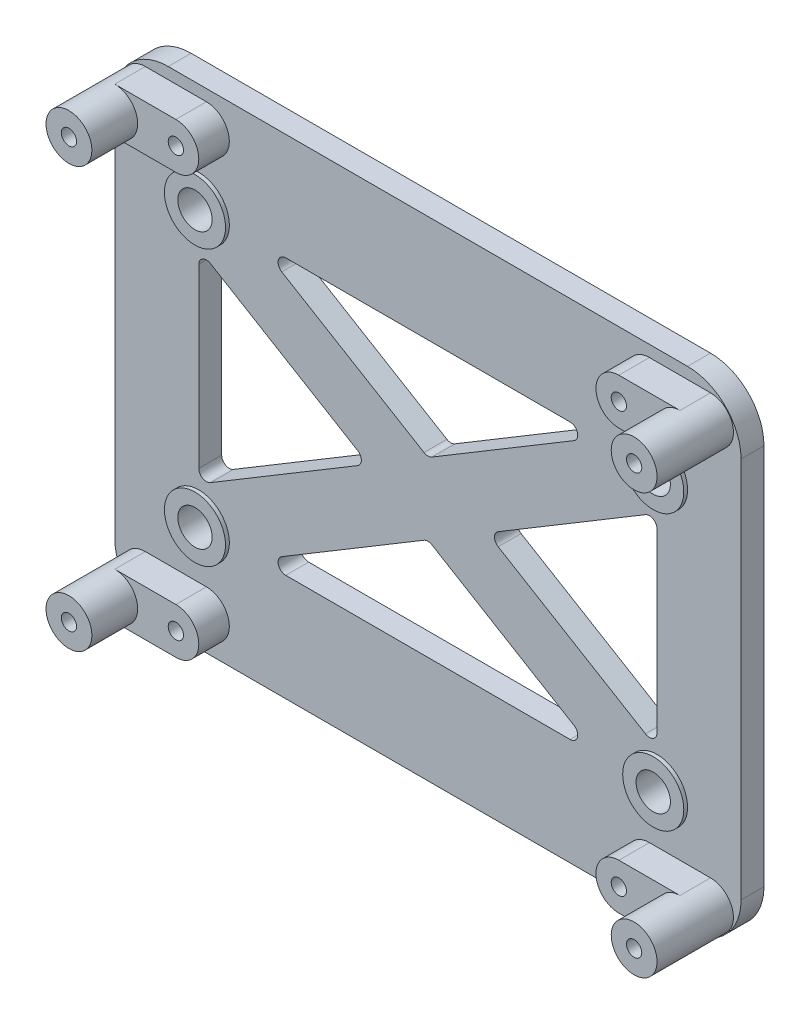
SolidWorks part; units mm, degrees
material "ABS"
ref_plane "Plano frontal" through (0, 0, 0) normal (0, 0, 1) x (1, 0, 0)
ref_plane "Plano superior" through (0, 0, 0) normal (0, 1, 0) x (1, 0, 0)
ref_plane "Plano direito" through (0, 0, 0) normal (1, 0, 0) x (0, 0, -1)
sketch "Esboço1" plane through (0, 0, 0) normal (0, 0, 1) x (1, 0, 0)
  line L1 (-41, -32) -> (41, -32)
  line L2 (-41, -32) -> (-41, 32)
  line L3 (-41, 32) -> (41, 32)
  line L4 (41, -32) -> (41, 32)
  line L5 (-41, -32) -> (41, 32) construction
  line L6 (-41, 32) -> (41, -32) construction
  point P0 (0, 0)
  dimension "D1" = 82
  dimension "D2" = 64
extrude "Ressalto-extrusão1" add sketch "Esboço1" along normal blind 3
sketch "Esboço2" plane through (0, 0, 3) normal (0, 0, 1) x (1, 0, 0)
  line L0 (0, 32) -> (0, -32) construction
  line L1 (41, 32) -> (-41, 32) construction
  line L2 (-41, -32) -> (41, -32) construction
  line L3 (-41, 0) -> (41, 0) construction
  line L4 (-41, 32) -> (-41, -32) construction
  line L5 (41, -32) -> (41, 32) construction
  circle A0 centre (-29, 27.5) radius 3
  circle A1 centre (-29, -27.5) radius 3
  circle A2 centre (29, -27.5) radius 3
  circle A3 centre (29, 27.5) radius 3
  circle A4 centre (-29, 27.5) radius 1
  circle A5 centre (29, 27.5) radius 1
  circle A6 centre (29, -27.5) radius 1
  circle A7 centre (-29, -27.5) radius 1
  dimension "D1" = 29
  dimension "D2" = 27.5
  dimension "D3" = 6
  dimension "D4" = 2
extrude "Ressalto-extrusão2" add sketch "Esboço2" along normal blind 4
sketch "Esboço3" plane through (0, 0, 3) normal (0, 0, 1) x (1, 0, 0)
  line L0 (0, 32) -> (0, -32) construction
  line L1 (41, 32) -> (-41, 32) construction
  line L2 (-41, -32) -> (41, -32) construction
  line L3 (-41, 0) -> (41, 0) construction
  line L4 (-41, 32) -> (-41, -32) construction
  line L5 (41, -32) -> (41, 32) construction
  circle A0 centre (-37, 27.5) radius 3
  circle A2 centre (-37, 27.5) radius 1
  circle A3 centre (37, 27.5) radius 1
  circle A4 centre (37, 27.5) radius 3
  circle A5 centre (37, -27.5) radius 3
  circle A6 centre (37, -27.5) radius 1
  circle A7 centre (-37, -27.5) radius 1
  circle A8 centre (-37, -27.5) radius 3
  dimension "D1" = 6
  dimension "D2" = 27.5
  dimension "D3" = 37
  dimension "D4" = 2
extrude "Ressalto-extrusão3" add sketch "Esboço3" along normal blind 10
sketch "Esboço4" plane through (0, 0, 3) normal (0, 0, 1) x (1, 0, 0)
  line L0 (0, 32) -> (0, -32) construction
  line L1 (41, 32) -> (-41, 32) construction
  line L2 (-41, -32) -> (41, -32) construction
  line L3 (-41, 0) -> (41, 0) construction
  line L4 (-41, 32) -> (-41, -32) construction
  line L5 (41, -32) -> (41, 32) construction
  circle A1 centre (-30, 18) radius 2.25
  circle A2 centre (30, 18) radius 2.25
  circle A5 centre (30, -18) radius 2.25
  circle A6 centre (-30, -18) radius 2.25
  dimension "D1" = 18
  dimension "D2" = 4.5
  dimension "D3" = 30
extrude "Corte-extrusão1" cut sketch "Esboço4" against normal through all
sketch "Esboço5" plane through (0, 0, 3) normal (0, 0, 1) x (1, 0, 0)
  line L0 (0, 32) -> (0, -32) construction
  line L1 (41, 32) -> (-41, 32) construction
  line L2 (-41, -32) -> (41, -32) construction
  line L3 (-41, 0) -> (41, 0) construction
  line L4 (-41, 32) -> (-41, -32) construction
  line L5 (41, -32) -> (41, 32) construction
  circle A0 centre (-30, 18) radius 2.25
  circle A1 centre (-30, 18) radius 4
  circle A2 centre (30, 18) radius 4
  circle A3 centre (30, 18) radius 2.25
  circle A4 centre (-30, -18) radius 4
  circle A5 centre (-30, -18) radius 2.25
  circle A6 centre (30, -18) radius 2.25
  circle A7 centre (30, -18) radius 4
  dimension "D1" = 8
  dimension "D2" = 4.5
extrude "Ressalto-extrusão4" add sketch "Esboço5" along normal blind 0.5
fillet "Filete1" radius 7 4 edges at (-41, -32, 1.5) (41, -32, 1.5) (41, 32, 1.5) (-41, 32, 1.5)
sketch "Esboço6" plane through (0, 0, 3) normal (0, 0, 1) x (1, 0, 0)
  line L0 (-30, 18) -> (30, -18) construction
  line L1 (-30, -18) -> (30, 18) construction
  line L2 (-30, 13.3352) -> (-7.7746, 0)
  line L3 (-22.2254, -18) -> (0, -4.6648)
  line L4 (-22.2254, 18) -> (0, 4.6648)
  line L5 (-30, -13.3352) -> (-7.7746, 0)
  line L6 (-22.2254, 18) -> (22.2254, 18)
  line L7 (-30, 13.3352) -> (-30, -13.3352)
  line L8 (-22.2254, -18) -> (22.2254, -18)
  line L9 (30, -13.3352) -> (30, 13.3352)
  line L10 (-27.942, 21.43) -> (32.058, -14.57) construction
  line L11 (-32.058, 14.57) -> (27.942, -21.43) construction
  line L12 (-32.058, -14.57) -> (27.942, 21.43) construction
  line L13 (-27.942, -21.43) -> (32.058, 14.57) construction
  line L14 (0, 4.6648) -> (22.2254, 18)
  line L15 (7.7746, 0) -> (30, 13.3352)
  line L16 (0, -4.6648) -> (22.2254, -18)
  line L17 (7.7746, 0) -> (30, -13.3352)
  dimension "D3" = 0
  dimension "D4" = 0
  dimension "D5" = 0
  dimension "D6" = 0
  dimension "D1" = 4
  dimension "D2" = 4
extrude "Corte-extrusão2" cut sketch "Esboço6" against normal through all
fillet "Filete2" radius 1 12 edges at (30, 13.3352, 1.5) (30, -13.3352, 1.5) (7.7746, 0, 1.5) (-22.2254, -18, 1.5) (22.2254, -18, 1.5) (0, -4.6648, 1.5) (-7.7746, 0, 1.5) (-30, -13.3352, 1.5) (-30, 13.3352, 1.5) (22.2254, 18, 1.5) (0, 4.6648, 1.5) (-22.2254, 18, 1.5)
sketch "Esboço7" plane through (0, 0, 3) normal (0, 0, 1) x (1, 0, 0)
  line L0 (-37, 30.5) -> (-29, 30.5)
  line L1 (-37, 24.5) -> (-29, 24.5)
  line L2 (0, 32) -> (0, -32) construction
  line L3 (34, 32) -> (-34, 32) construction
  line L4 (-34, -32) -> (34, -32) construction
  line L5 (-41, 0) -> (41, 0) construction
  line L6 (-41, 25) -> (-41, -25) construction
  line L7 (41, -25) -> (41, 25) construction
  line L8 (37, 24.5) -> (29, 24.5)
  line L9 (37, 30.5) -> (29, 30.5)
  line L10 (37, -30.5) -> (29, -30.5)
  line L11 (37, -24.5) -> (29, -24.5)
  line L12 (-37, -24.5) -> (-29, -24.5)
  line L13 (-37, -30.5) -> (-29, -30.5)
  arc A0 (-37, 30.5) -> (-37, 24.5) centre (-37, 27.5) ccw
  arc A1 (-29, 24.5) -> (-29, 30.5) centre (-29, 27.5) ccw
  circle A2 centre (-37, 27.5) radius 1
  circle A3 centre (-29, 27.5) radius 1
  circle A4 centre (29, 27.5) radius 1
  circle A5 centre (37, 27.5) radius 1
  arc A6 (29, 24.5) -> (29, 30.5) centre (29, 27.5) cw
  arc A7 (37, 30.5) -> (37, 24.5) centre (37, 27.5) cw
  arc A8 (37, -30.5) -> (37, -24.5) centre (37, -27.5) ccw
  arc A9 (29, -24.5) -> (29, -30.5) centre (29, -27.5) ccw
  circle A10 centre (37, -27.5) radius 1
  circle A11 centre (29, -27.5) radius 1
  circle A12 centre (-29, -27.5) radius 1
  circle A13 centre (-37, -27.5) radius 1
  arc A14 (-29, -24.5) -> (-29, -30.5) centre (-29, -27.5) cw
  arc A15 (-37, -30.5) -> (-37, -24.5) centre (-37, -27.5) cw
extrude "Ressalto-extrusão5" add sketch "Esboço7" along normal up to surface (4 mm away) up to face at (-32, -27.5, 7)
